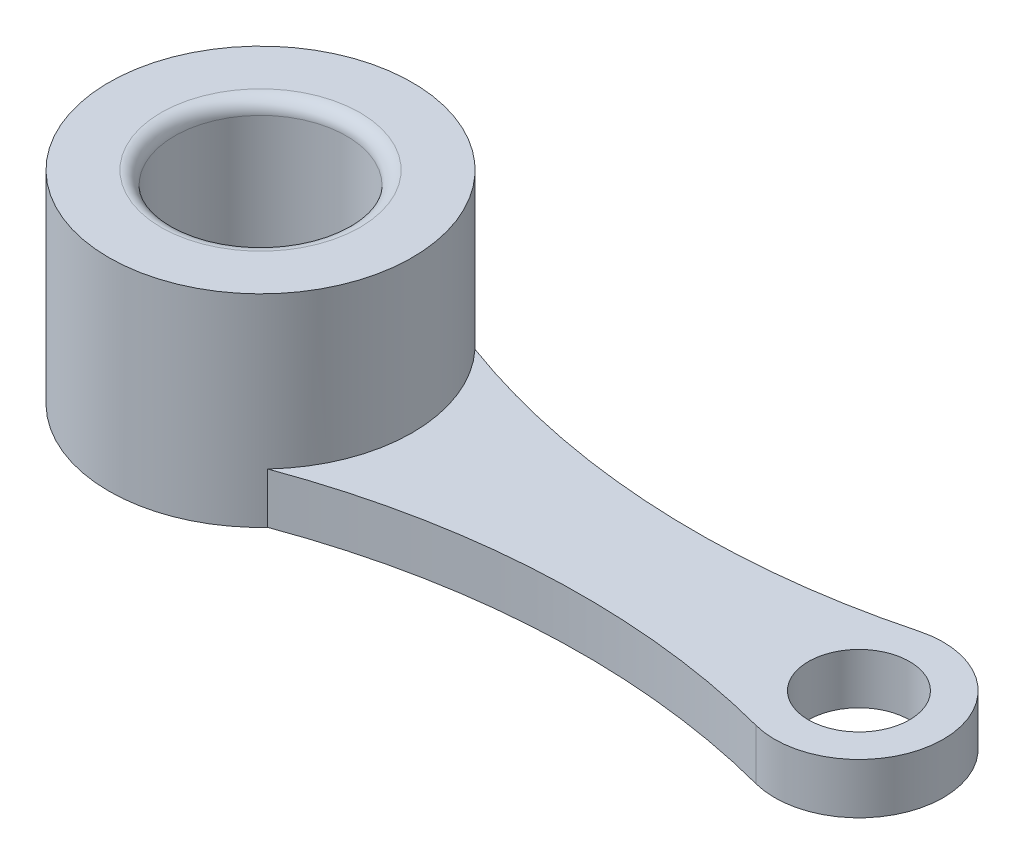
SolidWorks part; units mm, degrees
ref_plane "Front Plane" through (0, 0, 0) normal (0, 0, 1) x (1, 0, 0)
ref_plane "Top Plane" through (0, 0, 0) normal (0, 1, 0) x (1, 0, 0)
ref_plane "Right Plane" through (0, 0, 0) normal (1, 0, 0) x (0, 0, -1)
sketch "Sketch2" plane through (0, 0, 0) normal (0, 1, 0) x (1, 0, 0)
  line L0 (0, 0) -> (25, 0)
  line L1 (25, 0) -> (25, 9)
  line L2 (25, 9) -> (0, 9)
  line L3 (0, 9) -> (0, 0)
  line L4 (0, 4.5) -> (4.5, 4.5) construction
  line L5 (25, 4.5) -> (22.25, 4.5) construction
  dimension "D1" = 25
  dimension "D2" = 9
  dimension "D3" = 4.5
  dimension "D5" = 2.75
extrude "Boss-Extrude3" add sketch "Sketch2" along normal blind 6
sketch "Sketch3" plane through (0, 6, 0) normal (0, 1, 0) x (1, 0, 0)
  line L0 (0, 4.5) -> (4.5, 4.5) construction
  line L1 (0, 9) -> (0, 0) construction
  line L2 (25, 4.5) -> (22.25, 4.5) construction
  line L3 (25, 0) -> (25, 9) construction
  circle A0 centre (4.5, 4.5) radius 2.55
  circle A1 centre (22.25, 4.5) radius 1.75
  dimension "D3" = 5.1
  dimension "D4" = 3.5
  dimension "D1" = 4.5
  dimension "D2" = 2.75
extrude "Cut-Extrude1" cut sketch "Sketch3" against normal blind 5 contours A0
sketch "Sketch4" plane through (0, 6, 0) normal (0, 1, 0) x (1, 0, 0)
  line L0 (25, 4.5) -> (22.25, 4.5) construction
  line L1 (25, 0) -> (25, 9) construction
  circle A0 centre (22.25, 4.5) radius 1.5
  dimension "D2" = 3
  dimension "D1" = 2.75
extrude "Cut-Extrude2" cut sketch "Sketch4" against normal through all both and the other way through all
sketch "Sketch5" plane through (0, 6, 0) normal (0, 1, 0) x (1, 0, 0)
  line L0 (4.5, 9) -> (0, 9)
  line L1 (0, 9) -> (0, 4.5)
  line L2 (0, 4.5) -> (0, 0)
  line L3 (0, 0) -> (4.5, 0)
  line L4 (4.5, 0) -> (25, 0)
  line L5 (25, 0) -> (25, 9)
  line L6 (25, 9) -> (4.5, 9)
  circle A0 centre (4.5, 4.5) radius 4.5
  circle M9 centre (22.25, 4.5) radius 1.5
  line M12 (0, 0) -> (25, 0)
  line M13 (25, 0) -> (25, 9)
  line M14 (25, 9) -> (0, 9)
extrude "Cut-Extrude3" cut sketch "Sketch5" against normal blind 4.5 contours A0 M12 M13 M14 M9
sketch "Sketch6" plane through (0, 6, 0) normal (0, 1, 0) x (1, 0, 0)
  line L0 (4.5, 9) -> (0, 9)
  line L1 (0, 9) -> (0, 0)
  line L2 (0, 0) -> (4.5, 0)
  circle A0 centre (4.5, 4.5) radius 4.5
  line M2 (0, 0) -> (4.5, 0)
  line M4 (4.5, 9) -> (0, 9)
  line M5 (0, 9) -> (0, 0)
extrude "Cut-Extrude4" cut sketch "Sketch6" against normal through all contours A0 M4 M5 | A0 L1 M2
sketch "Sketch7" plane through (0, 6, 0) normal (0, 1, 0) x (1, 0, 0)
  circle A0 centre (4.5, 4.5) radius 2.8
  circle A2 centre (4.5, 4.5) radius 2.6
  dimension "D1" = 5.6
fillet "Fillet2" radius 0.4 1 edges at (4.5, 6, -1.95)
sketch "Sketch8" plane through (0, 0, 0) normal (0, -1, 0) x (1, 0, 0)
  circle A0 centre (4.5, -4.5) radius 1
  dimension "D1" = 2
extrude "Cut-Extrude5" cut sketch "Sketch8" against normal through all
sketch "Sketch9" plane through (0, 1.5, 0) normal (0, 1, 0) x (1, 0, 0)
  line L0 (4.5, 9) -> (25, 9)
  line L1 (25, 9) -> (25, 0)
  line L2 (25, 0) -> (4.5, 0)
  line L3 (9, 4.5) -> (15.2993, 4.5) construction
  line L6 (25, 1.4259) -> (25, 7.5741)
  line L7 (25, 0) -> (25, 9) construction
  line L8 (9, 4.5) -> (25, 0.9)
  line L9 (9, 4.5) -> (25, 8.1)
  line L10 (25, 8.1) -> (25, 0.9)
  line L11 (25, 8.1) -> (25, 9)
  line L12 (4.5, 9) -> (25, 9)
  line L13 (25, 0) -> (25, 0.9)
  line L14 (25, 0) -> (4.5, 0)
  line L15 (9, 4.5) -> (19.75, 4.5)
  line L16 (24.75, 4.5) -> (25, 4.5)
  circle A0 centre (22.25, 4.5) radius 2.5
  arc A1 (4.5, 9) -> (4.5, 0) centre (4.5, 4.5) cw
  arc A2 (25, 0.9) -> (7.7863, 1.4259) centre (15.7412, -20.1776) ccw
  arc A3 (25, 8.1) -> (7.7863, 7.5741) centre (15.7412, 29.1776) cw
  point P18 (25, 4.5)
  dimension "D1" = 5
  dimension "D2" = 3.6
extrude "Cut-Extrude7" cut sketch "Sketch9" against normal blind 10
